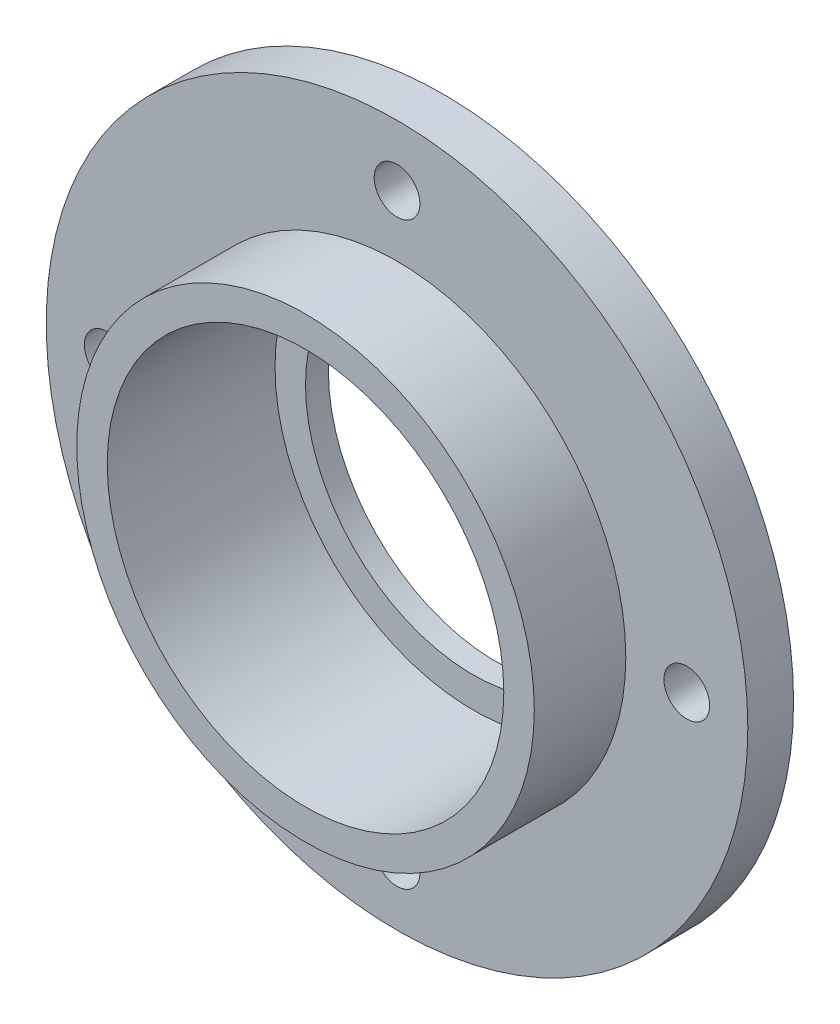
SolidWorks part; units mm, degrees
ref_plane "Front Plane" through (0, 0, 0) normal (0, 0, 1) x (1, 0, 0)
ref_plane "Top Plane" through (0, 0, 0) normal (0, 1, 0) x (1, 0, 0)
ref_plane "Right Plane" through (0, 0, 0) normal (1, 0, 0) x (0, 0, -1)
sketch "Sketch1" plane through (0, 0, 0) normal (0, 0, 1) x (1, 0, 0)
  circle A0 centre (0, 0) radius 13
  circle A1 centre (0, 0) radius 15
extrude "Boss-Extrude1" add sketch "Sketch1" along normal blind 7.5 and the other way blind 5
sketch "Sketch2" plane through (0, 0, 0) normal (0, 0, 1) x (1, 0, 0)
  circle A0 centre (0, 0) radius 23
  circle A1 centre (0, 0) radius 15
extrude "Boss-Extrude2" add sketch "Sketch2" along normal blind 1.5 and the other way blind 1.5
sketch "Sketch4" plane through (0, 0, -5) normal (0, 0, -1) x (-1, 0, 0)
  circle A0 centre (0, 0) radius 13
  circle A1 centre (0, 0) radius 11
extrude "Boss-Extrude3" add sketch "Sketch4" against normal blind 1.5
sketch "Sketch6" plane through (0, 0, 1.5) normal (0, 0, 1) x (1, 0, 0)
  circle A2 centre (0, 19) radius 1.5
  circle A3 centre (19, 0) radius 1.5
  circle A4 centre (0, -19) radius 1.5
  circle A5 centre (-19, 0) radius 1.5
  point P18 (0, 0)
  dimension "D1" = 4
extrude "Cut-Extrude1" cut sketch "Sketch6" against normal blind 10
